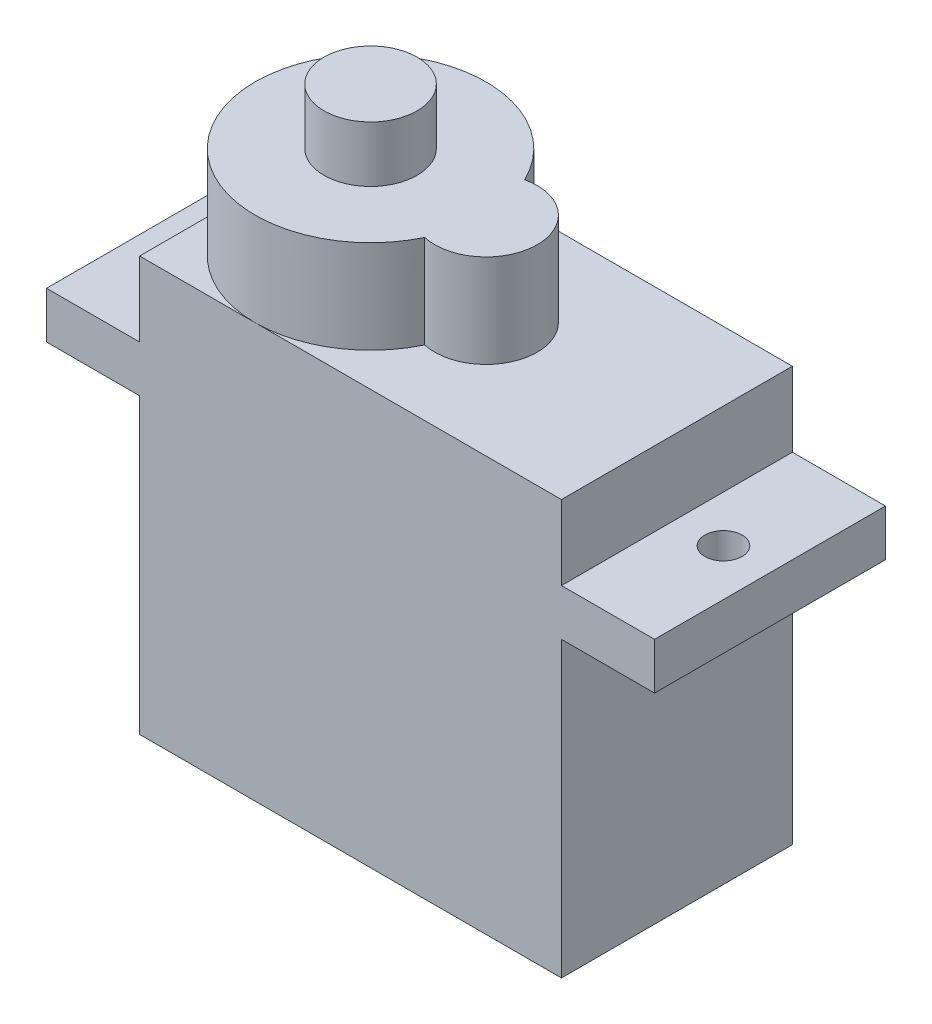
SolidWorks part; units mm, degrees
ref_plane "Alzado" through (0, 0, 0) normal (0, 0, 1) x (1, 0, 0)
ref_plane "Planta" through (0, 0, 0) normal (0, 1, 0) x (1, 0, 0)
ref_plane "Vista lateral" through (0, 0, 0) normal (1, 0, 0) x (0, 0, -1)
sketch "Croquis1" plane through (0, 0, 0) normal (0, 0, 1) x (1, 0, 0)
  line L0 (-22.65, 18.25) -> (-22.65, 22.25)
  line L1 (0, 0) -> (-22.65, 0)
  line L3 (0, 22.25) -> (-22.65, 22.25)
  line L4 (-22.65, 0) -> (-22.65, 15.75)
  line L5 (-22.65, 18.25) -> (-27.65, 18.25)
  line L7 (-22.65, 15.75) -> (-27.65, 15.75)
  line L8 (-27.65, 18.25) -> (-27.65, 15.75)
  line L9 (-11.325, 22.25) -> (-11.325, 0) construction
  line L10 (5, 18.25) -> (5, 15.75)
  line L11 (0, 15.75) -> (5, 15.75)
  line L12 (0, 18.25) -> (5, 18.25)
  line L13 (0, 0) -> (0, 15.75)
  line L14 (0, 18.25) -> (0, 22.25)
  dimension "D1" = 22.65
  dimension "D2" = 22.25
  dimension "D3" = 2.5
  dimension "D4" = 5
  dimension "D5" = 4
extrude "Saliente-Extruir1" add sketch "Croquis1" along normal blind 12.4
sketch "Croquis2" plane through (0, 22.25, 0) normal (0, 1, 0) x (1, 0, 0)
  line L2 (-22.65, -6.2) -> (-16.45, -6.2) construction
  line L3 (-22.65, -12.4) -> (-22.65, 0) construction
  line L4 (0, -12.4) -> (-22.65, -12.4) construction
  arc A0 (-10.8599, -3.5185) -> (-10.8599, -8.8815) centre (-16.45, -6.2) ccw
  arc A1 (-10.8599, -8.8815) -> (-10.8599, -3.5185) centre (-10.25, -6.2) ccw
  dimension "D1" = 5.5
extrude "Saliente-Extruir2" add sketch "Croquis2" along normal blind 5
sketch "Croquis3" plane through (0, 27.25, 0) normal (0, 1, 0) x (1, 0, 0)
  circle A0 centre (-16.45, -6.2) radius 2.5
extrude "Saliente-Extruir3" add sketch "Croquis3" along normal blind 3
sketch "Croquis4" plane through (-22.65, 0, 0) normal (-1, 0, 0) x (0, 0, 1)
  line L0 (6.2, 0) -> (6.2, 15.75) construction
  line L1 (4.2, 5.5) -> (8.2, 5.5)
  line L2 (4.2, 5.5) -> (4.2, 4.5)
  line L3 (4.2, 4.5) -> (8.2, 4.5)
  line L4 (8.2, 5.5) -> (8.2, 4.5)
  line L5 (12.4, 0) -> (0, 0) construction
  line L6 (12.4, 15.75) -> (0, 15.75) construction
  point P10 (6.2, 4.5)
  dimension "D1" = 4
  dimension "D2" = 1
  dimension "D3" = 4.5
extrude "Saliente-Extruir4" add sketch "Croquis4" along normal blind 3
sketch "Croquis5" plane through (0, 18.25, 0) normal (0, 1, 0) x (1, 0, 0)
  line L0 (-27.65, -12.4) -> (-27.65, 0) construction
  line L1 (5, -12.4) -> (5, 0) construction
  circle A0 centre (2.5, -6.2) radius 1
  circle A1 centre (-25.15, -6.2) radius 1
  dimension "D1" = 2
  dimension "D3" = 2
  dimension "D4" = 2.5
  dimension "D2" = 2.5
extrude "Cortar-Extruir1" cut sketch "Croquis5" against normal up to vertex (2.5 mm away)
